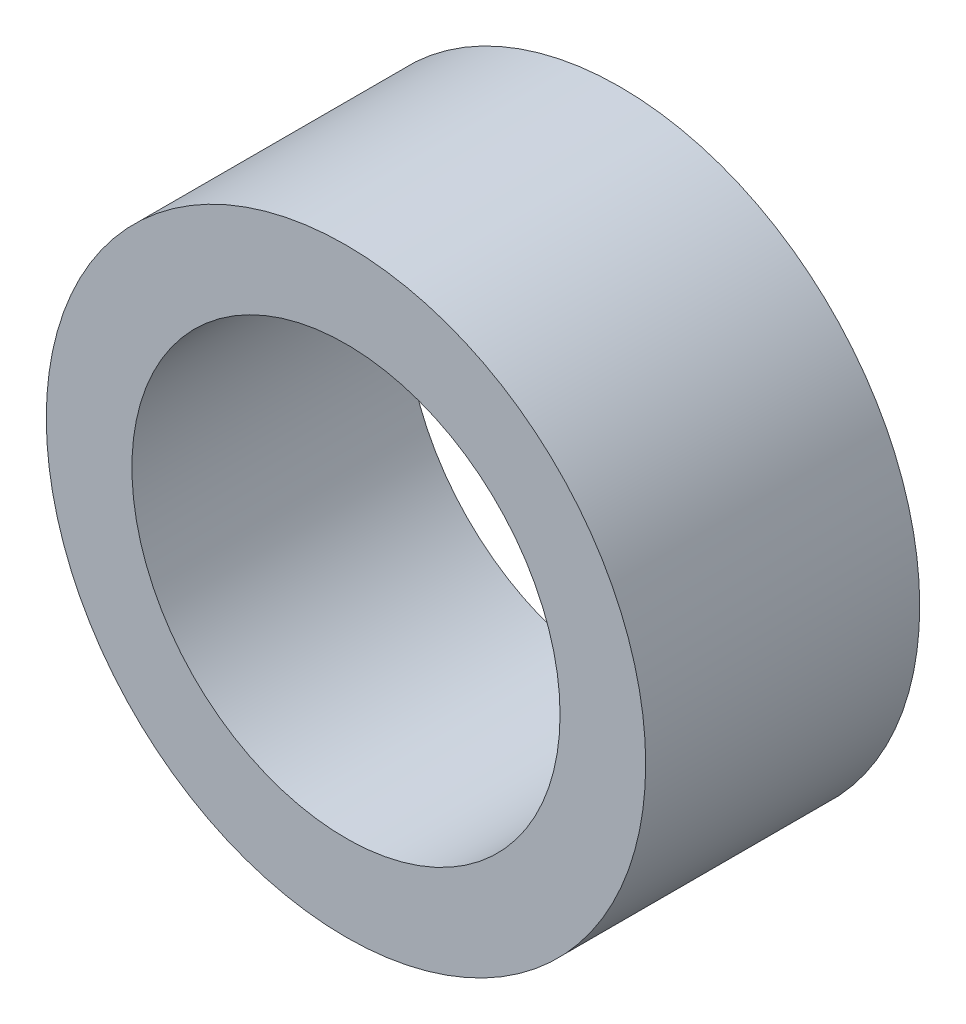
SolidWorks part; units mm, degrees
material "ABS"
ref_plane "Front Plane" through (0, 0, 0) normal (0, 0, 1) x (1, 0, 0)
ref_plane "Top Plane" through (0, 0, 0) normal (0, 1, 0) x (1, 0, 0)
ref_plane "Right Plane" through (0, 0, 0) normal (1, 0, 0) x (0, 0, -1)
sketch "Sketch1" plane through (0, 0, 0) normal (0, 0, 1) x (1, 0, 0)
  circle A4 centre (0, 0) radius 3.175
  circle A5 centre (0, 0) radius 4.445
  dimension "D1" = 6.35
  dimension "D2" = 1.27
extrude "Boss-Extrude1" add sketch "Sketch1" along normal blind 6.985
sketch "Sketch2" plane through (0, 0, 6.985) normal (0, 0, 1) x (1, 0, 0)
  circle A1 centre (0, 0) radius 4.445
  circle A2 centre (0, 0) radius 4.445
  dimension "D1" = 0
extrude "Cut-Extrude1" cut sketch "Sketch2" against normal blind 2.921
